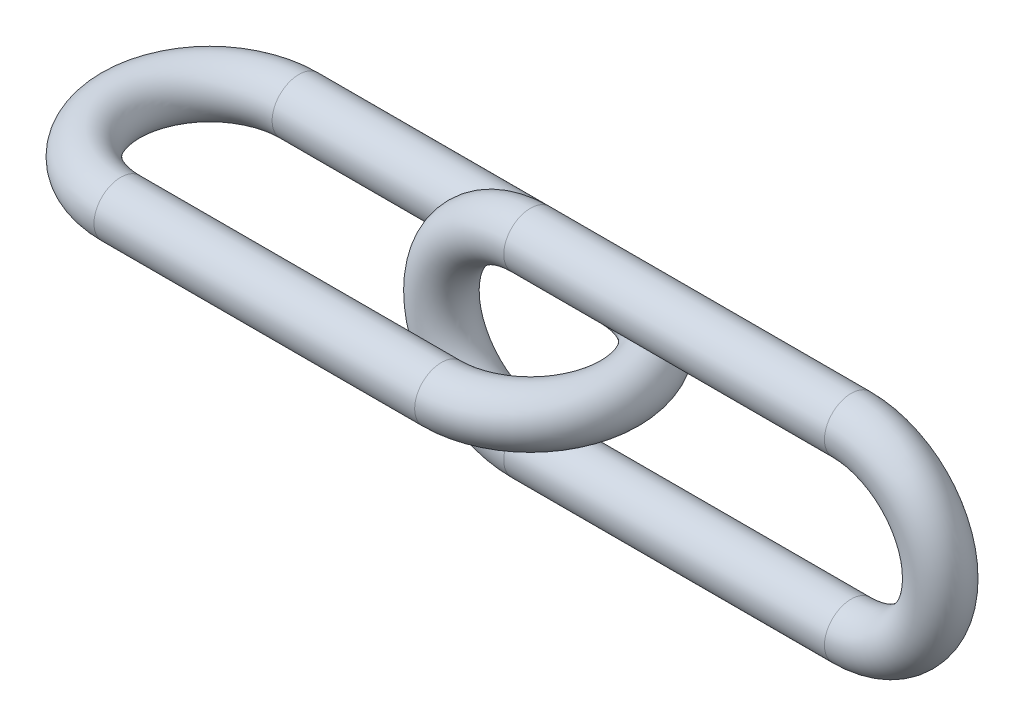
SolidWorks part; units mm, degrees
ref_plane "Front Plane" through (0, 0, 0) normal (0, 0, 1) x (1, 0, 0)
ref_plane "Top Plane" through (0, 0, 0) normal (0, 1, 0) x (1, 0, 0)
ref_plane "Right Plane" through (0, 0, 0) normal (1, 0, 0) x (0, 0, -1)
sketch "Sketch1" plane through (0, 0, 0) normal (0, 0, 1) x (1, 0, 0)
  line L0 (0, 0) -> (0, -207.672) construction
  line L1 (0, -207.672) -> (0, 198.1481) construction
  line L2 (0, -50) -> (180, -50)
  line L3 (0, 50) -> (180, 50)
  arc A0 (180, 50) -> (180, -50) centre (180, 0) cw
  arc A1 (0, 50) -> (0, -50) centre (0, 0) ccw
  dimension "D2" = 50
  dimension "D1" = 50
  dimension "D3" = 180
  dimension "D4" = 180
sketch "Sketch3" plane through (0, 0, 0) normal (1, 0, 0) x (0, 0, -1)
  circle A0 centre (0, 50) radius 15
  dimension "D1" = 30
sketch "Sketch4" plane through (0, 0, 0) normal (1, 0, 0) x (0, 0, -1)
  circle A0 centre (0, -50) radius 15
  dimension "D1" = 30
ref_plane "Plane1" through (180, 0, 0) normal (1, 0, 0) x (0, 0, -1)
sketch "Sketch30" plane through (180, 0, 0) normal (1, 0, 0) x (0, 0, -1)
  circle A0 centre (0, 50) radius 15
  circle A1 centre (0, -50) radius 15
  dimension "D1" = 30
  dimension "D2" = 30
extrude "Boss-Extrude3" add sketch "Sketch30" against normal up to surface (180 mm away) contours A0 up to plane "Right Plane"
extrude "Boss-Extrude4" add sketch "Sketch4" along normal up to surface (180 mm away) separate body contours A0 up to plane "Plane1"
sketch "Sketch57" plane through (0, 0, 0) normal (0, 1, 0) x (1, 0, 0)
  line L0 (0, 50) -> (-180, 50)
  line L1 (0, -155.8645) -> (0, 155.8645) construction
  line L2 (-170.1158, 0) -> (170.1158, 0) construction
  line L3 (0, -50) -> (-180, -50)
  arc A0 (-180, -50) -> (-180, 50) centre (-180, 0) cw
  dimension "D1" = 180
  dimension "D2" = 50
  dimension "D3" = 180
  dimension "D4" = 50
sketch "Sketch70" plane through (0, 0, 0) normal (0, 1, 0) x (1, 0, 0)
  point P0 (0, 50)
  point P1 (0, -50)
ref_plane "Plane2" through (-180, 0, 0) normal (1, 0, 0) x (0, 0, -1)
sketch "Sketch72" plane through (-180, 0, 0) normal (1, 0, 0) x (0, 0, -1)
  circle A0 centre (-50, 0) radius 15
  circle A1 centre (50, 0) radius 15
  dimension "D1" = 30
  dimension "D2" = 30
sketch "Sketch73" plane through (0, 0, 0) normal (1, 0, 0) x (0, 0, -1)
  circle A0 centre (-50, 0) radius 15
  circle A1 centre (50, 0) radius 15
  dimension "D1" = 30
  dimension "D2" = 30
extrude "Boss-Extrude5" add sketch "Sketch73" along direction (-1, 0, 0) on the side against the normal up to surface (180 mm away) separate body contours A1 up to plane "Plane2"
extrude "Boss-Extrude6" add sketch "Sketch72" along direction (-1, 0, 0) on the side of the normal up to surface (180 mm away) separate body contours A0 up to plane "Right Plane"
sketch "Sketch89" plane through (0, 0, 0) normal (0, 1, 0) x (1, 0, 0)
  arc A0 (0, 50) -> (0, -50) centre (0, 0) cw
sketch "Sketch90" plane through (0, 0, 0) normal (0, 1, 0) x (1, 0, 0)
  line L4 (180, 0) -> (180, 404.1767) construction
sketch "Sketch91" plane through (180, 0, 0) normal (1, 0, 0) x (0, 0, -1)
  line L0 (0, -207.672) -> (0, 198.1481) construction
  line L1 (0, 50) -> (0, -50) construction
  circle A0 centre (0, 50) radius 15
revolve "Revolve4" add sketch "Sketch91" angle 180 about L4
sketch "Sketch92" plane through (0, 0, 0) normal (-1, 0, 0) x (0, 0, 1)
  line L0 (0, 0) -> (-136.3161, 0) construction
  circle A0 centre (0, 50) radius 15
revolve "Revolve5" add sketch "Sketch92" angle 180 about L0
sketch "Sketch93" plane through (-180, 0, 0) normal (-1, 0, 0) x (0, 0, 1)
  line L0 (50, 0) -> (-50, 0) construction
  line L1 (0, 0) -> (-404.1767, 0) construction
  line L2 (-50, 0) -> (88.1779, 0) construction
  line L3 (0, 0) -> (0, 47.0547) construction
  circle A0 centre (-50, 0) radius 15
revolve "Revolve6" add sketch "Sketch93" angle 180 about L3
sketch "Sketch94" plane through (0, 0, 0) normal (1, 0, 0) x (0, 0, -1)
  line L0 (0, 0) -> (0, 28.7337) construction
  line L1 (0, -207.672) -> (0, 198.1481) construction
  circle A0 centre (50, 0) radius 15
revolve "Revolve7" add sketch "Sketch94" angle 180 about L0
